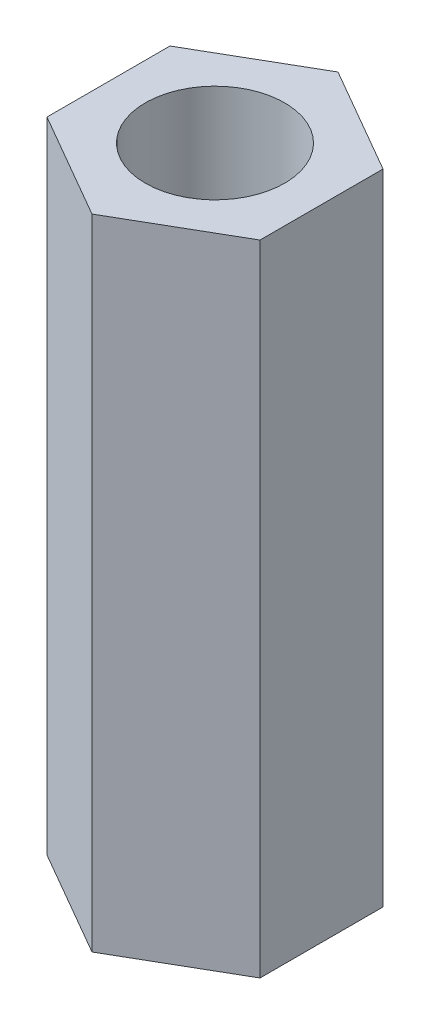
SolidWorks part; units mm, degrees
ref_plane "Front Plane" through (0, 0, 0) normal (0, 0, 1) x (1, 0, 0)
ref_plane "Top Plane" through (0, 0, 0) normal (0, 1, 0) x (1, 0, 0)
ref_plane "Right Plane" through (0, 0, 0) normal (1, 0, 0) x (0, 0, -1)
sketch "Sketch1" plane through (0, 0, 0) normal (0, 1, 0) x (1, 0, 0)
  line L0 (2.5002, 1.4435) -> (2.5002, -1.4435)
  line L1 (2.5002, -1.4435) -> (0, -2.887)
  line L2 (0, -2.887) -> (-2.5002, -1.4435)
  line L3 (-2.5002, -1.4435) -> (-2.5002, 1.4435)
  line L4 (-2.5002, 1.4435) -> (0, 2.887)
  line L5 (0, 2.887) -> (2.5002, 1.4435)
  circle A0 centre (0, 0) radius 1.635
  dimension "D1" = 3.27
  dimension "D3" = 2.887
  dimension "D4" = 2.887
  dimension "D5" = 2.887
  dimension "D6" = 2.887
  dimension "D7" = 2.887
extrude "Boss-Extrude1" add sketch "Sketch1" along normal blind 15
